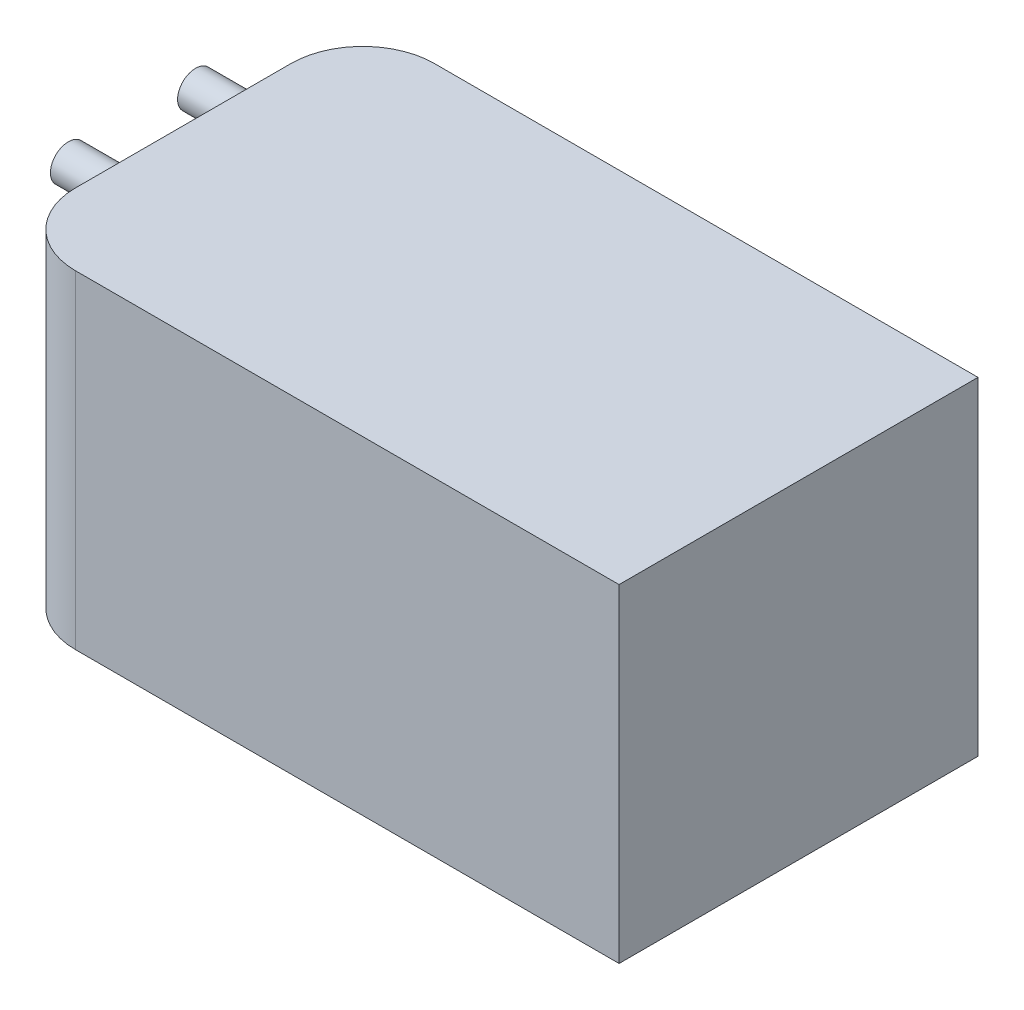
SolidWorks part; units mm, degrees
ref_plane "Front Plane" through (0, 0, 0) normal (0, 0, 1) x (1, 0, 0)
ref_plane "Top Plane" through (0, 0, 0) normal (0, 1, 0) x (1, 0, 0)
ref_plane "Right Plane" through (0, 0, 0) normal (1, 0, 0) x (0, 0, -1)
sketch "Sketch1" plane through (0, 0, 0) normal (0, 0, 1) x (1, 0, 0)
  line L1 (-30, -16) -> (30, -16)
  line L2 (-30, -16) -> (-30, 16)
  line L3 (-30, 16) -> (30, 16)
  line L4 (30, -16) -> (30, 16)
  line L5 (-30, -16) -> (30, 16) construction
  line L6 (-30, 16) -> (30, -16) construction
  point P0 (0, 0)
  dimension "D1" = 60
  dimension "D2" = 32
extrude "Boss-Extrude1" add sketch "Sketch1" along normal blind 35
fillet "Fillet1" radius 7 2 edges at (-30, 0, 0) (-30, 0, 35)
sketch "Sketch3" plane through (-30, 46, 0) normal (-1, 0, 0) x (0, 1, 0)
  line L0 (-32.5, -11.3) -> (-32.5, -23.7) construction
  line L1 (-30, -17.5) -> (-32.5, -17.5) construction
  line L2 (-30, -28) -> (-30, -7) construction
  circle A0 centre (-32.5, -11.3) radius 1.75
  circle A1 centre (-32.5, -23.7) radius 1.75
  point P8 (-32.5, -11.3)
  dimension "D1" = 3.5
extrude "Boss-Extrude3" add sketch "Sketch3" along normal blind 5
